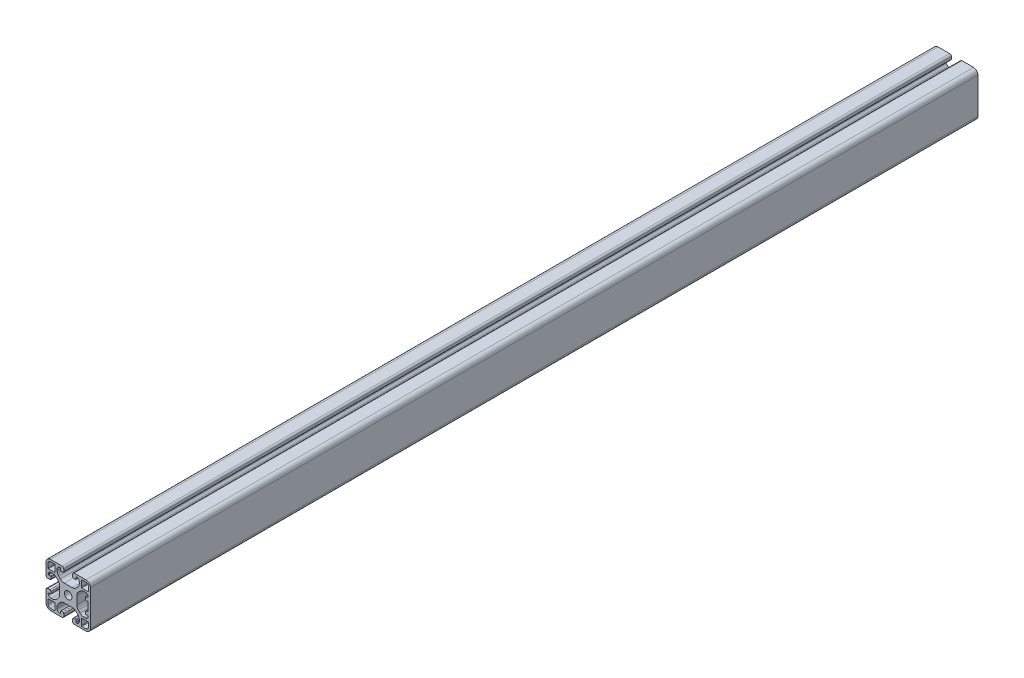
SolidWorks part; units mm, degrees
ref_plane "Piano frontale" through (0, 0, 0) normal (0, 0, 1) x (1, 0, 0)
ref_plane "Piano superiore" through (0, 0, 0) normal (0, 1, 0) x (1, 0, 0)
ref_plane "Piano destro" through (0, 0, 0) normal (1, 0, 0) x (0, 0, -1)
ref_plane "Piano1" through (0, 0, -340) normal (0, 0, -1) x (-1, 0, 0)
sketch "Schizzo1" plane through (0, 0, -340) normal (0, 0, -1) x (-1, 0, 0)
  line L0 (-12.3, -18.2) -> (-16, -18.2)
  line L1 (-18.2, -16) -> (-18.2, -12.3)
  line L2 (-17.7, -11.8) -> (-12.3, -11.8)
  line L3 (-11.8, -12.3) -> (-11.8, -17.7)
  line L4 (-11.8, 17.7) -> (-11.8, 12.3)
  line L5 (-12.3, 11.8) -> (-17.7, 11.8)
  line L6 (-18.2, 12.3) -> (-18.2, 16)
  line L7 (-16, 18.2) -> (-12.3, 18.2)
  line L8 (18.2, 16) -> (18.2, 12.3)
  line L9 (17.7, 11.8) -> (12.3, 11.8)
  line L10 (11.8, 12.3) -> (11.8, 17.7)
  line L11 (12.3, 18.2) -> (16, 18.2)
  line L12 (6.5, -15.5) -> (5, -15.5)
  line L13 (4, -16.5) -> (4, -18.5)
  line L14 (5.5, -20) -> (16, -20)
  line L15 (20, -16) -> (20, -5.5)
  line L16 (18.5, -4) -> (16.5, -4)
  line L17 (15.5, -5) -> (15.5, -6.5)
  line L18 (16, -7) -> (17.55, -7)
  line L19 (18, -7.45) -> (18, -7.5)
  line L20 (15.5, -10) -> (14.1924, -10)
  line L21 (10.6569, -8.5355) -> (9.2145, -7.0931)
  line L22 (7.75, -3.5576) -> (7.75, 3.5576)
  line L23 (9.2145, 7.0931) -> (10.6569, 8.5355)
  line L24 (14.1924, 10) -> (15.5, 10)
  line L25 (18, 7.5) -> (18, 7.45)
  line L26 (17.55, 7) -> (16, 7)
  line L27 (15.5, 6.5) -> (15.5, 5)
  line L28 (16.5, 4) -> (18.5, 4)
  line L29 (20, 5.5) -> (20, 16)
  line L30 (16, 20) -> (5.5, 20)
  line L31 (4, 18.5) -> (4, 16.5)
  line L32 (5, 15.5) -> (6.5, 15.5)
  line L33 (7, 16) -> (7, 17.55)
  line L34 (7.45, 18) -> (7.5, 18)
  line L35 (10, 15.5) -> (10, 14.1924)
  line L36 (8.5355, 10.6569) -> (7.0931, 9.2145)
  line L37 (3.5576, 7.75) -> (-3.5576, 7.75)
  line L38 (-7.0931, 9.2145) -> (-8.5355, 10.6569)
  line L39 (-10, 14.1924) -> (-10, 15.5)
  line L40 (-7.5, 18) -> (-7.45, 18)
  line L41 (-7, 17.55) -> (-7, 16)
  line L42 (-6.5, 15.5) -> (-5, 15.5)
  line L43 (-4, 16.5) -> (-4, 18.5)
  line L44 (-5.5, 20) -> (-16, 20)
  line L45 (-20, 16) -> (-20, -16)
  line L46 (-16, -20) -> (-5.5, -20)
  line L47 (-4, -18.5) -> (-4, -16.5)
  line L48 (-5, -15.5) -> (-6.5, -15.5)
  line L49 (-7, -16) -> (-7, -17.55)
  line L50 (-7.45, -18) -> (-7.5, -18)
  line L51 (-10, -15.5) -> (-10, -14.1924)
  line L52 (-8.5355, -10.6569) -> (-7.0931, -9.2145)
  line L53 (-3.5576, -7.75) -> (3.5576, -7.75)
  line L54 (7.0931, -9.2145) -> (8.5355, -10.6569)
  line L55 (10, -14.1924) -> (10, -15.5)
  line L56 (7.5, -18) -> (7.45, -18)
  line L57 (7, -17.55) -> (7, -16)
  line L58 (18.2, -12.3) -> (18.2, -16)
  line L59 (16, -18.2) -> (12.3, -18.2)
  line L60 (11.8, -17.7) -> (11.8, -12.3)
  line L61 (12.3, -11.8) -> (17.7, -11.8)
  line L62 (-16, 7) -> (-17.5, 7)
  line L63 (-15.5, 10) -> (-14.1924, 10)
  line L64 (-10.6569, 8.5355) -> (-9.2145, 7.0931)
  line L65 (-7.75, 3.5576) -> (-7.75, -3.5576)
  line L66 (-9.2145, -7.0931) -> (-10.6569, -8.5355)
  line L67 (-14.1924, -10) -> (-15.5, -10)
  line L68 (-17.5, -7) -> (-16, -7)
  line L69 (-15.5, -6.5) -> (-15.5, -5)
  line L70 (-16.5, -4) -> (-17.5, -4)
  line L71 (-18, -3.5) -> (-18, 3.5)
  line L72 (-17.5, 4) -> (-16.5, 4)
  line L73 (-15.5, 5) -> (-15.5, 6.5)
  arc A0 (-16, -18.2) -> (-18.2, -16) centre (-16, -16) cw
  arc A1 (-18.2, -12.3) -> (-17.7, -11.8) centre (-17.7, -12.3) cw
  arc A2 (-12.3, -11.8) -> (-11.8, -12.3) centre (-12.3, -12.3) cw
  arc A3 (-11.8, -17.7) -> (-12.3, -18.2) centre (-12.3, -17.7) cw
  arc A4 (-12.3, 18.2) -> (-11.8, 17.7) centre (-12.3, 17.7) cw
  arc A5 (-11.8, 12.3) -> (-12.3, 11.8) centre (-12.3, 12.3) cw
  arc A6 (-17.7, 11.8) -> (-18.2, 12.3) centre (-17.7, 12.3) cw
  arc A7 (-18.2, 16) -> (-16, 18.2) centre (-16, 16) cw
  arc A8 (16, 18.2) -> (18.2, 16) centre (16, 16) cw
  arc A9 (18.2, 12.3) -> (17.7, 11.8) centre (17.7, 12.3) cw
  arc A10 (12.3, 11.8) -> (11.8, 12.3) centre (12.3, 12.3) cw
  arc A11 (11.8, 17.7) -> (12.3, 18.2) centre (12.3, 17.7) cw
  arc A12 (5, -15.5) -> (4, -16.5) centre (5, -16.5) ccw
  arc A13 (4, -18.5) -> (5.5, -20) centre (5.5, -18.5) ccw
  arc A14 (16, -20) -> (20, -16) centre (16, -16) ccw
  arc A15 (20, -5.5) -> (18.5, -4) centre (18.5, -5.5) ccw
  arc A16 (16.5, -4) -> (15.5, -5) centre (16.5, -5) ccw
  arc A17 (15.5, -6.5) -> (16, -7) centre (16, -6.5) ccw
  arc A18 (17.55, -7) -> (18, -7.45) centre (17.55, -7.45) cw
  arc A19 (18, -7.5) -> (15.5, -10) centre (15.5, -7.5) cw
  arc A20 (14.1924, -10) -> (10.6569, -8.5355) centre (14.1924, -5) cw
  arc A21 (9.2145, -7.0931) -> (7.75, -3.5576) centre (12.75, -3.5576) cw
  arc A22 (7.75, 3.5576) -> (9.2145, 7.0931) centre (12.75, 3.5576) cw
  arc A23 (10.6569, 8.5355) -> (14.1924, 10) centre (14.1924, 5) cw
  arc A24 (15.5, 10) -> (18, 7.5) centre (15.5, 7.5) cw
  arc A25 (18, 7.45) -> (17.55, 7) centre (17.55, 7.45) cw
  arc A26 (16, 7) -> (15.5, 6.5) centre (16, 6.5) ccw
  arc A27 (15.5, 5) -> (16.5, 4) centre (16.5, 5) ccw
  arc A28 (18.5, 4) -> (20, 5.5) centre (18.5, 5.5) ccw
  arc A29 (20, 16) -> (16, 20) centre (16, 16) ccw
  arc A30 (5.5, 20) -> (4, 18.5) centre (5.5, 18.5) ccw
  arc A31 (4, 16.5) -> (5, 15.5) centre (5, 16.5) ccw
  arc A32 (6.5, 15.5) -> (7, 16) centre (6.5, 16) ccw
  arc A33 (7, 17.55) -> (7.45, 18) centre (7.45, 17.55) cw
  arc A34 (7.5, 18) -> (10, 15.5) centre (7.5, 15.5) cw
  arc A35 (10, 14.1924) -> (8.5355, 10.6569) centre (5, 14.1924) cw
  arc A36 (7.0931, 9.2145) -> (3.5576, 7.75) centre (3.5576, 12.75) cw
  arc A37 (-3.5576, 7.75) -> (-7.0931, 9.2145) centre (-3.5576, 12.75) cw
  arc A38 (-8.5355, 10.6569) -> (-10, 14.1924) centre (-5, 14.1924) cw
  arc A39 (-10, 15.5) -> (-7.5, 18) centre (-7.5, 15.5) cw
  arc A40 (-7.45, 18) -> (-7, 17.55) centre (-7.45, 17.55) cw
  arc A41 (-7, 16) -> (-6.5, 15.5) centre (-6.5, 16) ccw
  arc A42 (-5, 15.5) -> (-4, 16.5) centre (-5, 16.5) ccw
  arc A43 (-4, 18.5) -> (-5.5, 20) centre (-5.5, 18.5) ccw
  arc A44 (-16, 20) -> (-20, 16) centre (-16, 16) ccw
  arc A45 (-20, -16) -> (-16, -20) centre (-16, -16) ccw
  arc A46 (-5.5, -20) -> (-4, -18.5) centre (-5.5, -18.5) ccw
  arc A47 (-4, -16.5) -> (-5, -15.5) centre (-5, -16.5) ccw
  arc A48 (-6.5, -15.5) -> (-7, -16) centre (-6.5, -16) ccw
  arc A49 (-7, -17.55) -> (-7.45, -18) centre (-7.45, -17.55) cw
  arc A50 (-7.5, -18) -> (-10, -15.5) centre (-7.5, -15.5) cw
  arc A51 (-10, -14.1924) -> (-8.5355, -10.6569) centre (-5, -14.1924) cw
  arc A52 (-7.0931, -9.2145) -> (-3.5576, -7.75) centre (-3.5576, -12.75) cw
  arc A53 (3.5576, -7.75) -> (7.0931, -9.2145) centre (3.5576, -12.75) cw
  arc A54 (8.5355, -10.6569) -> (10, -14.1924) centre (5, -14.1924) cw
  arc A55 (10, -15.5) -> (7.5, -18) centre (7.5, -15.5) cw
  arc A56 (7.45, -18) -> (7, -17.55) centre (7.45, -17.55) cw
  arc A57 (7, -16) -> (6.5, -15.5) centre (6.5, -16) ccw
  arc A58 (17.7, -11.8) -> (18.2, -12.3) centre (17.7, -12.3) cw
  arc A59 (18.2, -16) -> (16, -18.2) centre (16, -16) cw
  arc A60 (12.3, -18.2) -> (11.8, -17.7) centre (12.3, -17.7) cw
  arc A61 (11.8, -12.3) -> (12.3, -11.8) centre (12.3, -12.3) cw
  circle A62 centre (0, 0) radius 3.4
  arc A63 (-15.5, 6.5) -> (-16, 7) centre (-16, 6.5) ccw
  arc A64 (-17.5, 7) -> (-18, 7.5) centre (-17.5, 7.5) cw
  arc A65 (-18, 7.5) -> (-15.5, 10) centre (-15.5, 7.5) cw
  arc A66 (-14.1924, 10) -> (-10.6569, 8.5355) centre (-14.1924, 5) cw
  arc A67 (-9.2145, 7.0931) -> (-7.75, 3.5576) centre (-12.75, 3.5576) cw
  arc A68 (-7.75, -3.5576) -> (-9.2145, -7.0931) centre (-12.75, -3.5576) cw
  arc A69 (-10.6569, -8.5355) -> (-14.1924, -10) centre (-14.1924, -5) cw
  arc A70 (-15.5, -10) -> (-18, -7.5) centre (-15.5, -7.5) cw
  arc A71 (-18, -7.5) -> (-17.5, -7) centre (-17.5, -7.5) cw
  arc A72 (-16, -7) -> (-15.5, -6.5) centre (-16, -6.5) ccw
  arc A73 (-15.5, -5) -> (-16.5, -4) centre (-16.5, -5) ccw
  arc A74 (-17.5, -4) -> (-18, -3.5) centre (-17.5, -3.5) cw
  arc A75 (-18, 3.5) -> (-17.5, 4) centre (-17.5, 3.5) cw
  arc A76 (-16.5, 4) -> (-15.5, 5) centre (-16.5, 5) ccw
extrude "Estrusione-Estrusione1" add sketch "Schizzo1" against normal blind 800
